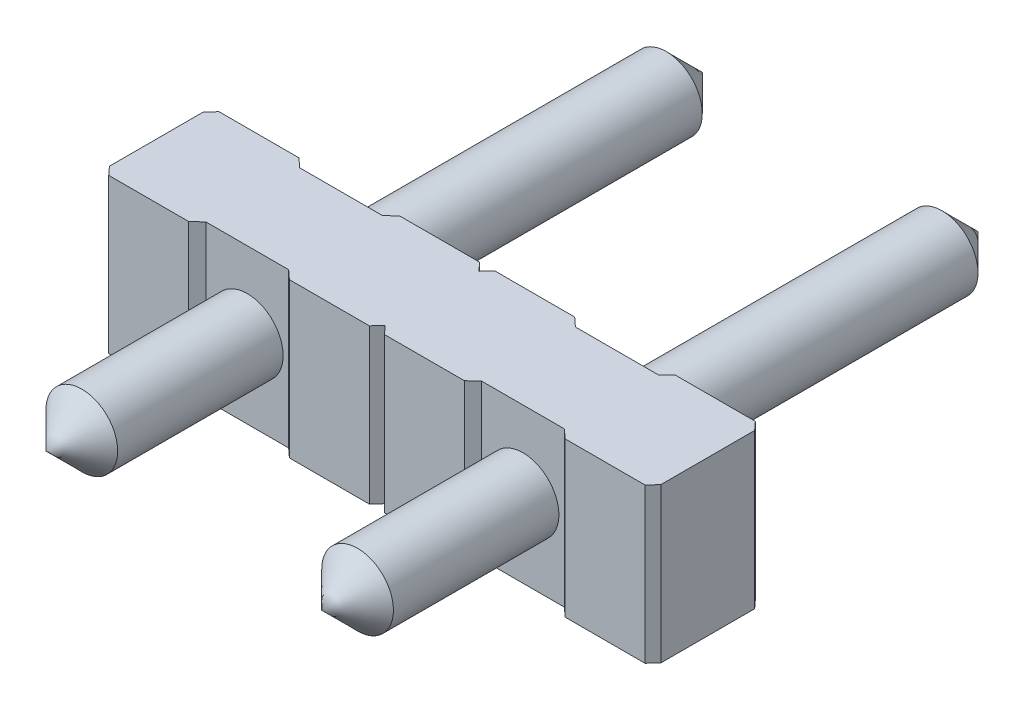
SolidWorks part; units mm, degrees
ref_plane "Front Plane" through (0, 0, 0) normal (0, 0, 1) x (1, 0, 0)
ref_plane "Top Plane" through (0, 0, 0) normal (0, 1, 0) x (1, 0, 0)
ref_plane "Right Plane" through (0, 0, 0) normal (1, 0, 0) x (0, 0, -1)
sketch "Sketch1" plane through (0, 0, 0) normal (0, 1, 0) x (1, 0, 0)
  line L0 (-3.4902, 0) -> (4.2792, 0) construction
  line L1 (-2.5, -0.85) -> (-2.5, 0.85)
  line L2 (-2.5, 0.85) -> (-2.3627, 1)
  line L3 (-2.3627, 1) -> (-0.9138, 1)
  line L4 (-0.9138, 1) -> (-0.75, 0.85)
  line L5 (-0.75, 0.85) -> (0.75, 0.85)
  line L6 (0, 1.7) -> (0, 0) construction
  line L7 (2.5, -0.85) -> (2.5, 0.85)
  line L8 (0.9138, 1) -> (0.75, 0.85)
  line L9 (2.3627, 1) -> (0.9138, 1)
  line L10 (2.5, 0.85) -> (2.3627, 1)
  line L11 (2.5, -0.85) -> (2.3627, -1)
  line L12 (2.3627, -1) -> (0.9138, -1)
  line L13 (0.9138, -1) -> (0.75, -0.85)
  line L14 (-0.75, -0.85) -> (0.75, -0.85)
  line L15 (-0.9138, -1) -> (-0.75, -0.85)
  line L16 (-2.3627, -1) -> (-0.9138, -1)
  line L17 (-2.5, -0.85) -> (-2.3627, -1)
  point P3 (-2.5, 0.9027)
  point P11 (0, 0)
  point P12 (0, 0)
  point P14 (0, 0.85)
  point P22 (2.5, 0)
  point P26 (-2.5, 0)
  point P27 (-2.5, 0.7208)
  point P28 (-0.75, 0.6753)
  point P29 (-2.0638, 1)
  point P30 (-1.0458, 1)
  point P31 (-2.037, 1)
  point P32 (-0.8228, 1)
  dimension "D1" = 2.5
  dimension "D2" = 0.75
  dimension "D3" = 1
  dimension "D4" = 0.85
extrude "Boss-Extrude1" add sketch "Sketch1" along normal mid plane 2.8
sketch "Sketch2" plane through (0, 0, -0.85) normal (0, 0, -1) x (-1, 0, 0)
  circle A0 centre (0, 0) radius 0.65
  point P0 (0, 0)
  dimension "D1" = 1.3
extrude "Boss-Extrude2" add sketch "Sketch2" along normal blind 5.9
sketch "Sketch3" plane through (0, 0, 0.85) normal (0, 0, 1) x (1, 0, 0)
  circle A0 centre (0, 0) radius 0.65
  dimension "D1" = 1.3
extrude "Boss-Extrude3" add sketch "Sketch3" along normal blind 3
sketch "Sketch5" plane through (0, 0, 3.85) normal (0, 0, 1) x (1, 0, 0)
  circle A1 centre (0, 0) radius 0.65
  circle A2 centre (0, 0) radius 0.65
  dimension "D1" = 0
extrude "Boss-Extrude4" add sketch "Sketch5" along normal blind 0.75 draft 45
sketch "Sketch6" plane through (0, 0, -6.75) normal (0, 0, -1) x (-1, 0, 0)
  circle A1 centre (0, 0) radius 0.65
  circle A2 centre (0, 0) radius 0.65
  dimension "D1" = 0
extrude "Boss-Extrude5" add sketch "Sketch6" along normal blind 0.75 draft 45
mirror "Mirror1" about plane through (-2.5, 1.4, 0.85) normal (1, 0, 0) of bodies 105
